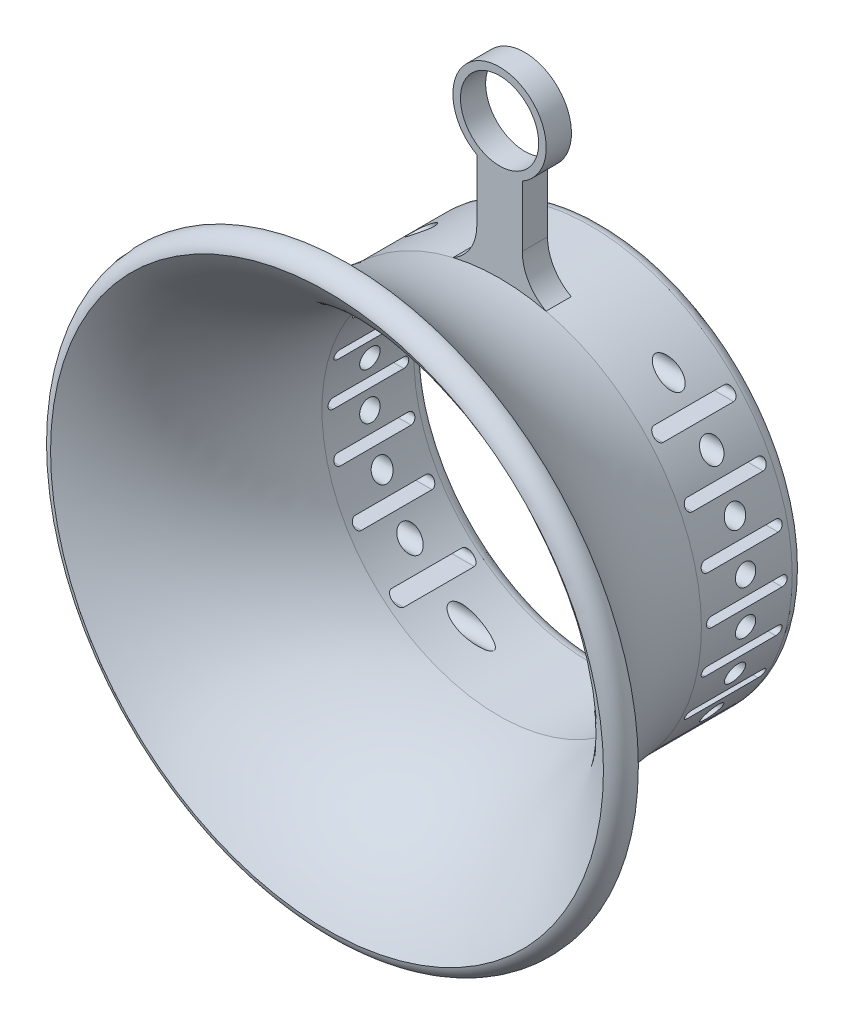
SolidWorks part; units mm, degrees
other "Markup1"
sketch "Sketch2" plane through (-67.8261, 67.8261, 51.0537) normal (-0.7784, 0.528, 0.3396) x (0.4925, 0.1782, 0.8519)
ref_plane "Front Plane" through (0, 0, 0) normal (0, 0, 1) x (1, 0, 0)
ref_plane "Top Plane" through (0, 0, 0) normal (0, 1, 0) x (1, 0, 0)
ref_plane "Right Plane" through (0, 0, 0) normal (1, 0, 0) x (0, 0, -1)
sketch "Sketch1" plane through (0, 0, 0) normal (1, 0, 0) x (0, 0, -1)
  line L0 (-41.2359, 0) -> (64.2513, 0) construction
  line L1 (-3.0414, 40) -> (-21.0414, 40)
  line L2 (-3.0414, 35) -> (-21.2462, 35)
  arc A1 (-3.0414, 40) -> (-3.0414, 35) centre (-3.0414, 37.5) cw
  arc A3 (-55.2419, 54.7879) -> (-51.0414, 57.5) centre (-51.7856, 54.0437) cw
  spline S0 degree 2 poles (-21.0414, 40) (-40.7891, 41.6209) (-51.0414, 57.5) knots 0 0 0 1 1 1
  spline S1 degree 1 poles (-21.2462, 35) (-55.2419, 54.7879) knots 0 0 1 1 construction
  spline S2 degree 2 poles (-21.2462, 35) (-21.4782, 35.0186) (-21.9913, 35.0631) (-22.7489, 35.1361) (-24.2546, 35.3087) (-27.2099, 35.7605) (-32.8997, 37.0968) (-41.0109, 40.5533) (-50.9489, 48.1087) (-55.2419, 54.7879) knots -0.00517 -0.00517 -0.00517 0.00661 0.018389 0.041948 0.089065 0.1833 0.371769 0.623061 1 1 1
  point P12 (-48.613, 61.2637)
  point P13 (-38.5414, 45.2594)
  point P16 (-50.5181, 58.0489)
  point P17 (-51.299, 55.3185)
  point P18 (-40.0615, 47.5)
  point P19 (-21.5167, 35)
  point P20 (-51.7227, 53.7722)
  dimension "D1" = 5
  dimension "D2" = 35
  dimension "D3" = 47.5
  dimension "D4" = 18
  dimension "D5" = 30
ref_plane "Plane1" through (60, 0, 0) normal (1, 0, 0) x (0, 0, -1)
ref_plane "Plane2" through (0, 0, 47) normal (0, 0, 1) x (1, 0, 0)
sketch "Sketch7" plane through (0, 0, 47) normal (0, 0, 1) x (1, 0, 0)
  line L0 (-110.1572, 0) -> (149.0132, 0) construction
revolve "Revolve2" add sketch "Sketch1" angle 360 about L0
ref_plane "Plane3" through (0, 0, 21.05) normal (0, 0, 1) x (1, 0, 0)
sketch "Sketch10" plane through (0, 0, 21.05) normal (0, 0, 1) x (1, 0, 0)
  line L0 (87.9675, 0) -> (-94.9823, 0) construction
  line L1 (0, -81.874) -> (0, -57.75) construction
  line L2 (-4.5, 58.9184) -> (-4.5, 46.8358)
  line L3 (4.5, 58.9184) -> (4.5, 46.8358)
  line L4 (-4.5, -58.9184) -> (-4.5, -46.8358)
  line L5 (4.5, -58.9184) -> (4.5, -46.8358)
  line L6 (0, -39.9) -> (0, 88.5413) construction
  circle A0 centre (0, 0) radius 39.9
  circle A1 centre (0, 0) radius 67
  circle A2 centre (0, 67) radius 7.75
  circle A3 centre (0, 67) radius 9.25
  arc A4 (-4.5, 46.8358) -> (-12.4995, 37.8916) centre (-13.5, 46.8358) cw
  arc A5 (4.5, 46.8358) -> (12.4995, 37.8916) centre (13.5, 46.8358) ccw
  arc A6 (-4.5, -46.8358) -> (-12.4995, -37.8916) centre (-13.5, -46.8358) ccw
  arc A7 (4.5, -46.8358) -> (12.4995, -37.8916) centre (13.5, -46.8358) cw
  circle A10 centre (0, -67) radius 9.25
  circle A11 centre (0, -67) radius 7.75
  dimension "D1" = 4.5
  dimension "D3" = 15.5
  dimension "D4" = 18.5
  dimension "D5" = 134
  dimension "D6" = 9
  dimension "D2" = 79.8
extrude "Boss-Extrude4" add sketch "Sketch10" against normal blind 5 contours A1 A11 A10 | A1 A11 A10 | L4 A10 L5 A7 A0 A6 | A5 L3 A3 L2 A4 A0 | A1 A3 A2 | A1 A3 A2
ref_plane "Plane4" through (60, 0, 0) normal (1, 0, 0) x (0, 0, -1)
sketch "Sketch11" plane through (60, 0, 0) normal (1, 0, 0) x (0, 0, -1)
  line L0 (-89.4247, 0) -> (27.1429, 0) construction
  line L1 (-19.0414, 0) -> (-5.0414, 0) construction
  line L2 (-19.0414, 1) -> (-5.0414, 1)
  line L3 (-19.0414, -1) -> (-5.0414, -1)
  line L4 (-21.0414, -38.9262) -> (-21.0414, 38.9262) construction
  line L5 (-19.0414, 9) -> (-5.0414, 9) construction
  line L6 (-19.0414, 10) -> (-5.0414, 10)
  line L7 (-19.0414, 8) -> (-5.0414, 8)
  line L8 (-19.0414, 18) -> (-5.0414, 18) construction
  line L9 (-19.0414, 19) -> (-5.0414, 19)
  line L10 (-19.0414, 17) -> (-5.0414, 17)
  line L11 (-19.0414, 27) -> (-5.0414, 27) construction
  line L12 (-19.0414, 28) -> (-5.0414, 28)
  line L13 (-19.0414, 26) -> (-5.0414, 26)
  line L14 (-19.0414, -9) -> (-5.0414, -9) construction
  line L15 (-19.0414, -10) -> (-5.0414, -10)
  line L16 (-19.0414, -8) -> (-5.0414, -8)
  line L17 (-19.0414, -18) -> (-5.0414, -18) construction
  line L18 (-19.0414, -19) -> (-5.0414, -19)
  line L19 (-19.0414, -17) -> (-5.0414, -17)
  line L20 (-19.0414, -27) -> (-5.0414, -27) construction
  line L21 (-19.0414, -28) -> (-5.0414, -28)
  line L22 (-19.0414, -26) -> (-5.0414, -26)
  arc A0 (-19.0414, 1) -> (-19.0414, -1) centre (-19.0414, 0) ccw
  arc A1 (-5.0414, -1) -> (-5.0414, 1) centre (-5.0414, 0) ccw
  arc A2 (-19.0414, 10) -> (-19.0414, 8) centre (-19.0414, 9) ccw
  arc A3 (-5.0414, 8) -> (-5.0414, 10) centre (-5.0414, 9) ccw
  arc A4 (-19.0414, 19) -> (-19.0414, 17) centre (-19.0414, 18) ccw
  arc A5 (-5.0414, 17) -> (-5.0414, 19) centre (-5.0414, 18) ccw
  arc A6 (-19.0414, 28) -> (-19.0414, 26) centre (-19.0414, 27) ccw
  arc A7 (-5.0414, 26) -> (-5.0414, 28) centre (-5.0414, 27) ccw
  arc A8 (-19.0414, -10) -> (-19.0414, -8) centre (-19.0414, -9) cw
  arc A9 (-5.0414, -8) -> (-5.0414, -10) centre (-5.0414, -9) cw
  arc A10 (-19.0414, -19) -> (-19.0414, -17) centre (-19.0414, -18) cw
  arc A11 (-5.0414, -17) -> (-5.0414, -19) centre (-5.0414, -18) cw
  arc A12 (-19.0414, -28) -> (-19.0414, -26) centre (-19.0414, -27) cw
  arc A13 (-5.0414, -26) -> (-5.0414, -28) centre (-5.0414, -27) cw
  point P5 (-12.0414, 0)
  point P15 (-12.0414, 9)
  point P22 (-12.0414, 18)
  point P29 (-12.0414, 27)
  point P35 (-12.0414, -9)
  point P42 (-12.0414, -18)
  point P49 (-12.0414, -27)
  dimension "D1" = 9
  dimension "D2" = 4
extrude "Cut-Extrude1" cut sketch "Sketch11" against normal through all both and the other way through all
sketch "Sketch12" plane through (60, 0, 0) normal (1, 0, 0) x (0, 0, -1)
  line L0 (-21.0414, -38.9262) -> (-21.0414, 38.9262) construction
  line L1 (-19.0414, 1) -> (-5.0414, 1) construction
  circle A0 centre (-12.0414, 4.5) radius 2
  circle A1 centre (-12.0414, 13.5) radius 2
  circle A2 centre (-12.0414, 22.5) radius 2
  circle A3 centre (-12.0414, 31.5) radius 2
  circle A4 centre (-12.0414, -4.5) radius 2
  circle A5 centre (-12.0414, -13.5) radius 2
  circle A6 centre (-12.0414, -22.5) radius 2
  circle A7 centre (-12.0414, -31.5) radius 2
  dimension "D1" = 9
  dimension "D2" = 3.5
  dimension "D3" = 4
  dimension "D4" = 5
extrude "Cut-Extrude2" cut sketch "Sketch12" against normal through all both and the other way through all
